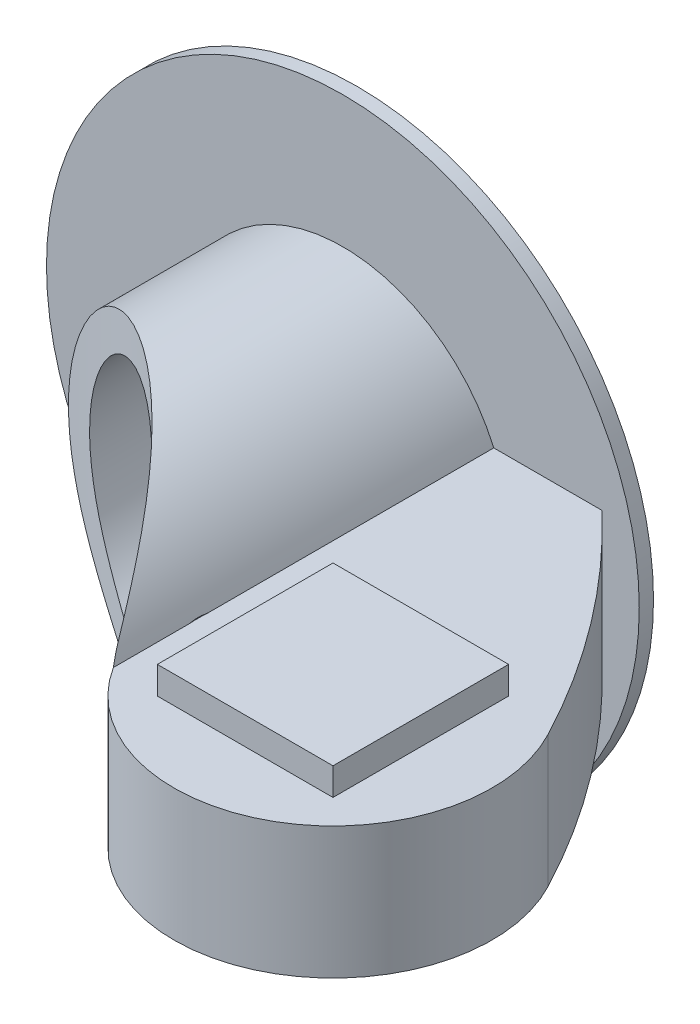
SolidWorks part; units mm, degrees
ref_plane "前视基准面" through (0, 0, 0) normal (0, 0, 1) x (1, 0, 0)
ref_plane "上视基准面" through (0, 0, 0) normal (0, 1, 0) x (1, 0, 0)
ref_plane "右视基准面" through (0, 0, 0) normal (1, 0, 0) x (0, 0, -1)
sketch "草图1" plane through (0, 0, 0) normal (0, 0, 1) x (1, 0, 0)
  circle A0 centre (0, 0) radius 270
  dimension "D1" = 540
extrude "凸台-拉伸1" add sketch "草图1" along normal blind 13
sketch "草图2" plane through (0, 0, 0) normal (0, 0, 1) x (1, 0, 0)
  circle A0 centre (0, 0) radius 150
  circle A1 centre (0, 0) radius 120
  dimension "D1" = 300
  dimension "D2" = 240
extrude "凸台-拉伸2" add sketch "草图2" along normal blind 400
sketch "草图4" plane through (0, 0, 0) normal (0, 1, 0) x (1, 0, 0)
  line L0 (-150, -13) -> (150, -13) construction
  line L1 (-297.9124, -638.1843) -> (-297.9124, 206.5668) construction
  line L2 (-270, -13) -> (270, -13) construction
  line L4 (-150, -13) -> (-150, -400) construction
  line L5 (-150, -400) -> (175.7326, -400)
  line L6 (-150, -400) -> (150, -400) construction
  line L7 (-150, -400) -> (-150, -113)
  circle A0 centre (260, -282) radius 145
  arc A1 (131.6401, -349.4444) -> (-150, -113) centre (-297.9124, -575.1451) ccw
  arc A2 (388.3599, -214.5556) -> (235.9296, -13) centre (-297.9124, -575.1451) ccw
  dimension "D1" = 269
  dimension "D3" = 290
  dimension "D4" = 100
  dimension "D2" = 260
extrude "切除-拉伸1" cut sketch "草图4" against normal mid plane 440 contours A0 A1 L7 L5
sketch "草图5" plane through (0, 0, 0) normal (0, 1, 0) x (1, 0, 0)
  line L2 (131.6401, -13) -> (235.9296, -13)
  line L4 (131.6401, -349.4444) -> (131.6401, -13)
  line L5 (-270, -13) -> (270, -13) construction
  arc A0 (388.3599, -214.5556) -> (235.9296, -13) centre (-297.9124, -575.1451) ccw construction
  circle A1 centre (260, -282) radius 145
  arc A2 (131.6401, -349.4444) -> (388.3599, -214.5556) centre (260, -282) ccw
  arc A4 (388.3599, -214.5556) -> (235.9296, -13) centre (-297.9124, -575.1451) ccw
  dimension "D1" = 0
extrude "凸台-拉伸3" add sketch "草图5" along normal mid plane 120
sketch3d "3D草图6"
  circle A0 centre (0, 0, -50) radius 206.805
  point P2 (0, 0, -256.805)
sketch "草图27" plane through (0, 0, 13) normal (0, 0, 1) x (1, 0, 0)
  line L1 (-82.5, -82.5) -> (82.5, -82.5)
  line L2 (-82.5, -82.5) -> (-82.5, 82.5)
  line L3 (-82.5, 82.5) -> (82.5, 82.5)
  line L4 (82.5, -82.5) -> (82.5, 82.5)
  line L5 (-82.5, -82.5) -> (82.5, 82.5) construction
  line L6 (-82.5, 82.5) -> (82.5, -82.5) construction
  point P0 (0, 0)
  dimension "D1" = 165
  dimension "D2" = 165
extrude "凸台-拉伸14" add sketch "草图27" along normal blind 30
sketch "草图45" plane through (0, 60, 0) normal (0, 1, 0) x (1, 0, 0)
  line L1 (137.4773, -13) -> (137.4773, -359.5447)
  line L3 (235.9296, -13) -> (137.4773, -13)
  line L4 (235.9296, -13) -> (137.4773, -13)
  line L5 (137.4773, -13) -> (137.4773, -359.5447)
  circle A0 centre (260, -282) radius 122.82
  arc A1 (388.3599, -214.5556) -> (235.9296, -13) centre (-297.9124, -575.1451) ccw
  arc A2 (388.3599, -214.5556) -> (235.9296, -13) centre (-297.9124, -575.1451) ccw
  circle A3 centre (260, -282) radius 122.82
  arc A6 (137.4773, -359.5447) -> (388.3599, -214.5556) centre (260, -282) ccw
  arc A7 (137.4773, -359.5447) -> (388.3599, -214.5556) centre (260, -282) ccw
  dimension "D1" = 0
sketch "草图51" plane through (0, 60, 0) normal (0, 1, 0) x (1, 0, 0)
  line L1 (137.4773, -13) -> (137.4773, -359.5447)
  line L2 (137.4773, -13) -> (137.4773, -359.5447)
  line L4 (235.9296, -13) -> (137.4773, -13)
  line L5 (235.9296, -13) -> (137.4773, -13)
  circle A0 centre (260, -282) radius 122.82
  arc A1 (388.3599, -214.5556) -> (235.9296, -13) centre (-297.9124, -575.1451) ccw
  arc A2 (388.3599, -214.5556) -> (235.9296, -13) centre (-297.9124, -575.1451) ccw
  arc A5 (137.4773, -359.5447) -> (388.3599, -214.5556) centre (260, -282) ccw
  arc A6 (137.4773, -359.5447) -> (388.3599, -214.5556) centre (260, -282) ccw
  dimension "D1" = 0
extrude "切除-拉伸20" cut sketch "草图51" along normal blind 25
sketch "草图52" plane through (0, 60, 0) normal (0, 1, 0) x (1, 0, 0)
  line L1 (180, -362) -> (340, -362)
  line L2 (180, -362) -> (180, -202)
  line L3 (180, -202) -> (340, -202)
  line L4 (340, -362) -> (340, -202)
  line L5 (180, -362) -> (340, -202) construction
  line L6 (180, -202) -> (340, -362) construction
  point P0 (260, -282)
  dimension "D1" = 160
  dimension "D2" = 160
extrude "凸台-拉伸33" add sketch "草图52" along normal blind 25
ref_plane "基准面1" through (0, -60, 0) normal (0, -1, 0) x (-1, 0, 0)
sketch "草图53" plane through (0, -60, 0) normal (0, -1, 0) x (-1, 0, 0)
  circle A0 centre (-260, -282) radius 50
extrude "凸台-拉伸34" add sketch "草图53" along normal blind 10
